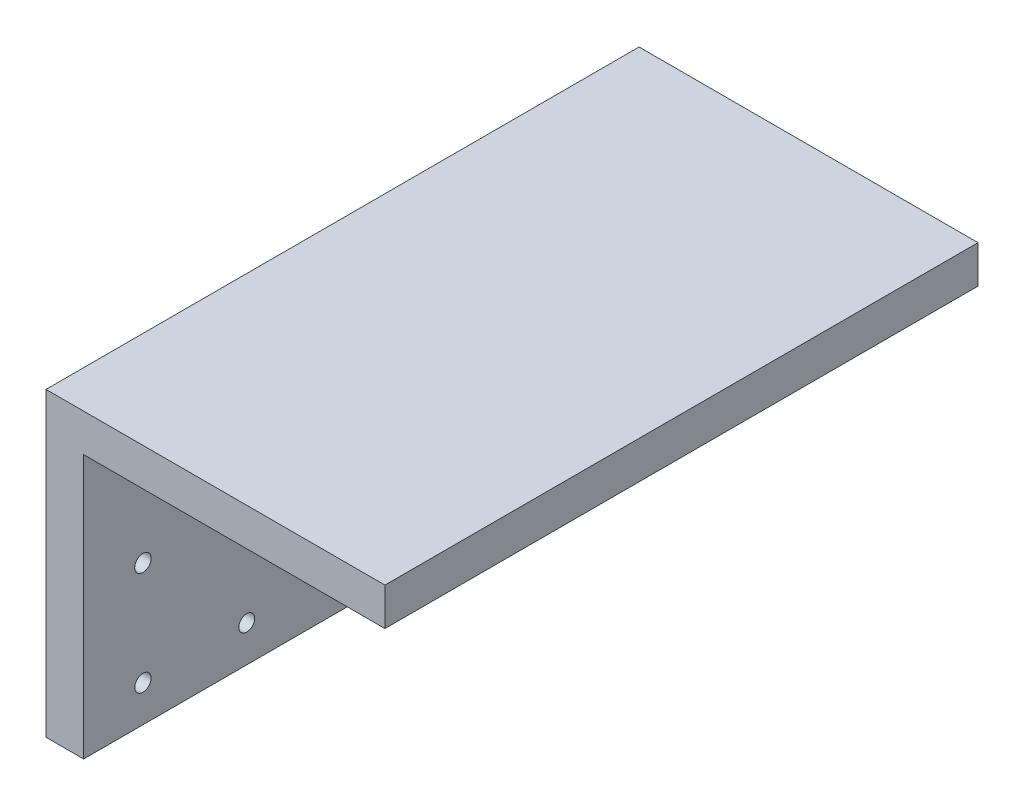
SolidWorks part; units mm, degrees
material "Aleación 1060"
ref_plane "Alzado" through (0, 0, 0) normal (0, 0, 1) x (1, 0, 0)
ref_plane "Planta" through (0, 0, 0) normal (0, 1, 0) x (1, 0, 0)
ref_plane "Vista lateral" through (0, 0, 0) normal (1, 0, 0) x (0, 0, -1)
sketch "Croquis1" plane through (0, 0, 0) normal (1, 0, 0) x (0, 0, -1)
  line L1 (100, -50.8) -> (-100, -50.8)
  line L2 (100, -50.8) -> (100, 50.8)
  line L3 (100, 50.8) -> (-100, 50.8)
  line L4 (-100, -50.8) -> (-100, 50.8)
  line L5 (100, -50.8) -> (-100, 50.8) construction
  line L6 (100, 50.8) -> (-100, -50.8) construction
  point P0 (0, 0)
  dimension "D1" = 200
  dimension "D2" = 101.6
extrude "Saliente-Extruir1" add sketch "Croquis1" along normal blind 12.7
sketch "Croquis2" plane through (12.7, 0, 0) normal (1, 0, 0) x (0, 0, -1)
  line L0 (100, -50.8) -> (100, 50.8) construction
  line L1 (-100, 50.8) -> (100, 50.8)
  line L2 (-100, 50.8) -> (-100, 38.1)
  line L3 (-100, 38.1) -> (100, 38.1)
  line L4 (100, 50.8) -> (100, 38.1)
  dimension "D1" = 12.7
extrude "Saliente-Extruir2" add sketch "Croquis2" along normal blind 101.6
sketch "Croquis3" plane through (12.7, 0, 0) normal (1, 0, 0) x (0, 0, -1)
  line L1 (-80, -38.5261) -> (-45, -38.5261) construction
  line L2 (-80, -38.5261) -> (-80, -3.5261) construction
  line L3 (-80, -3.5261) -> (-45, -3.5261) construction
  line L4 (-45, -38.5261) -> (-45, -3.5261) construction
  line L5 (40, -35) -> (75, -35) construction
  line L6 (40, -35) -> (40, 0) construction
  line L7 (40, 0) -> (75, 0) construction
  line L8 (75, -35) -> (75, 0) construction
  circle A0 centre (-80, -3.5261) radius 2.7839
  circle A1 centre (-45, -3.5261) radius 2.8396
  circle A2 centre (-80, -38.5261) radius 2.759
  circle A3 centre (-45, -38.5261) radius 2.6865
  circle A4 centre (40, 0) radius 2.8373
  circle A5 centre (75, 0) radius 2.9278
  circle A6 centre (40, -35) radius 2.6255
  circle A7 centre (75, -35) radius 2.716
  dimension "D1" = 35
  dimension "D2" = 35
  dimension "D3" = 35
  dimension "D4" = 35
  dimension "D5" = 120
  dimension "D6" = 80
extrude "Cortar-Extruir1" cut sketch "Croquis3" against normal blind 101.6
